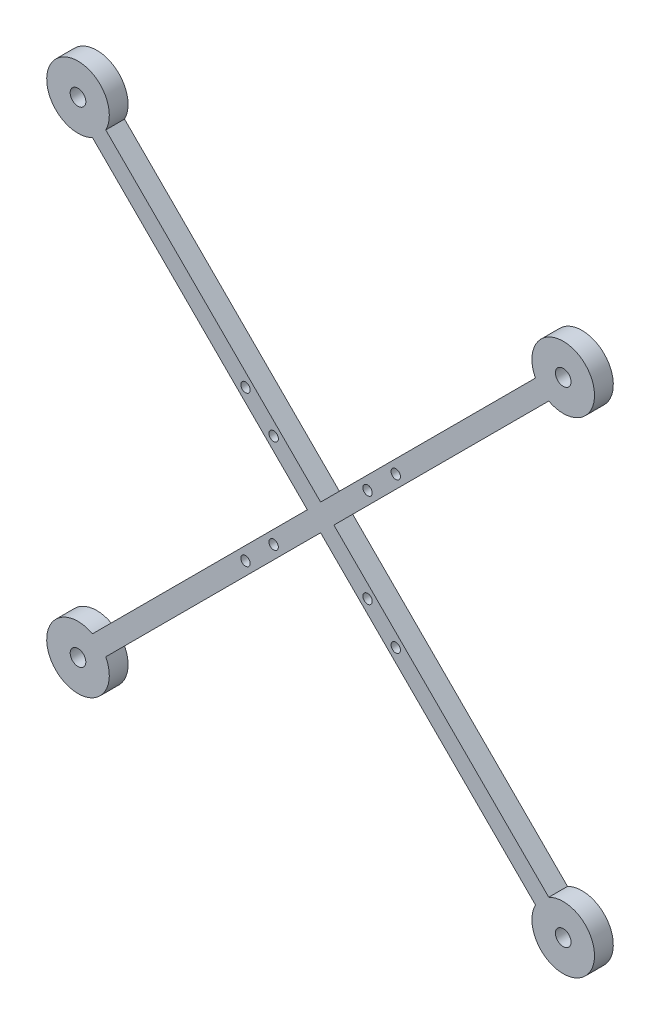
SolidWorks part; units mm, degrees
material "Carbon Fiber"
ref_plane "Front Plane" through (0, 0, 0) normal (0, 0, 1) x (1, 0, 0)
ref_plane "Top Plane" through (0, 0, 0) normal (0, 1, 0) x (1, 0, 0)
ref_plane "Right Plane" through (0, 0, 0) normal (1, 0, 0) x (0, 0, -1)
sketch "Sketch1" plane through (0, 0, 0) normal (0, 0, 1) x (1, 0, 0)
  line L0 (-77.5, 77.5) -> (77.5, 77.5) construction
  line L1 (77.5, 77.5) -> (77.5, -77.5) construction
  line L2 (-77.5, 77.5) -> (-77.5, -77.5) construction
  line L3 (-77.5, -77.5) -> (77.5, -77.5) construction
  line L4 (-77.5, 77.5) -> (77.5, -77.5) construction
  line L5 (77.5, 77.5) -> (-77.5, -77.5) construction
  line L6 (-68.6333, 72.876) -> (0, 4.2426)
  line L7 (-72.876, 68.6333) -> (-4.2426, 0)
  line L8 (0, 4.2426) -> (0, 77.5)
  line L9 (72.876, 68.6333) -> (4.2426, 0)
  line L10 (68.6333, 72.876) -> (0, 4.2426)
  line L11 (68.6333, -72.876) -> (0, -4.2426)
  line L12 (72.876, -68.6333) -> (4.2426, 0)
  line L13 (-72.876, -68.6333) -> (-4.2426, 0)
  line L14 (-68.6333, -72.876) -> (0, -4.2426)
  arc A0 (-68.6333, 72.876) -> (-72.876, 68.6333) centre (-77.5, 77.5) ccw
  circle A1 centre (-24, 24) radius 1.5
  circle A2 centre (-15, 15) radius 1.5
  circle A3 centre (-77.5, 77.5) radius 2.5
  arc A4 (72.876, 68.6333) -> (68.6333, 72.876) centre (77.5, 77.5) ccw
  circle A5 centre (24, 24) radius 1.5
  circle A6 centre (15, 15) radius 1.5
  circle A7 centre (77.5, 77.5) radius 2.5
  arc A8 (68.6333, -72.876) -> (72.876, -68.6333) centre (77.5, -77.5) ccw
  circle A9 centre (24, -24) radius 1.5
  circle A10 centre (15, -15) radius 1.5
  circle A11 centre (77.5, -77.5) radius 2.5
  arc A12 (-72.876, -68.6333) -> (-68.6333, -72.876) centre (-77.5, -77.5) ccw
  circle A13 centre (-24, -24) radius 1.5
  circle A14 centre (-15, -15) radius 1.5
  circle A15 centre (-77.5, -77.5) radius 2.5
  point P2 (0, 0)
  point P13 (0, 77.5)
  point P56 (0, 0)
  dimension "D5" = 3
  dimension "D7" = 3
  dimension "D8" = 5
  dimension "D10" = 10
  dimension "D1" = 155
  dimension "D2" = 155
  dimension "D3" = 6
  dimension "D4" = 24
  dimension "D6" = 15
  dimension "D9" = 4
extrude "Boss-Extrude1" add sketch "Sketch1" along normal blind 6 contours L13 A12 L14 L11 A8 L12 L9 A4 L10 L6 A0 L7 A15 A14 A13 A1 A2 A3 A5 A6 A7 A9 A10 A11
